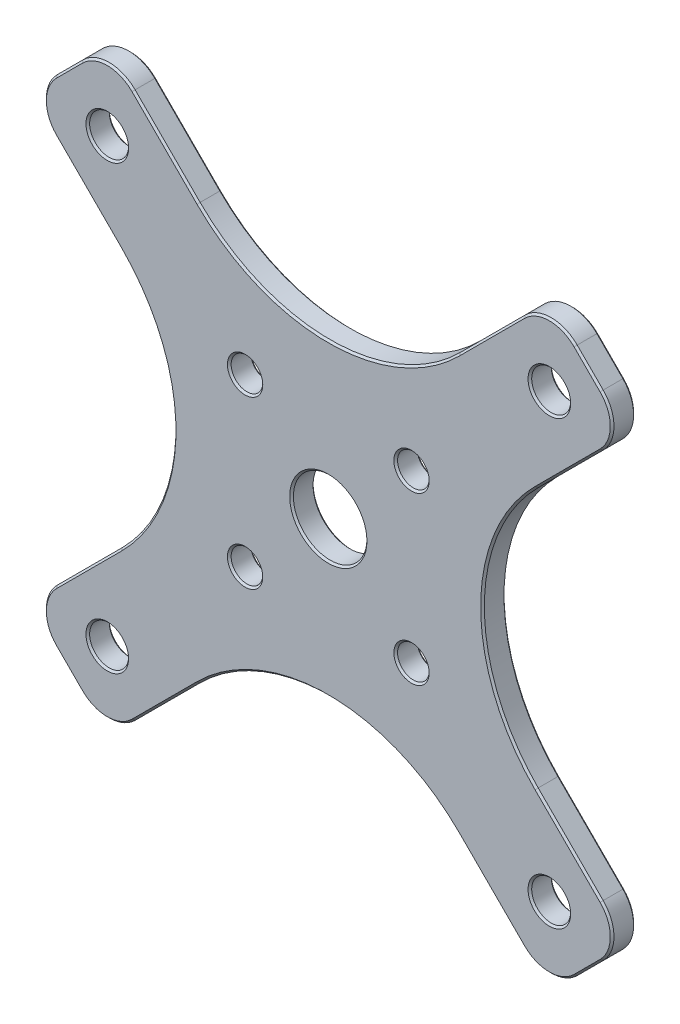
SolidWorks part; units mm, degrees
ref_plane "Front Plane" through (0, 0, 0) normal (0, 0, 1) x (1, 0, 0)
ref_plane "Top Plane" through (0, 0, 0) normal (0, 1, 0) x (1, 0, 0)
ref_plane "Right Plane" through (0, 0, 0) normal (1, 0, 0) x (0, 0, -1)
sketch "Sketch1" plane through (0, 0, 0) normal (0, 0, 1) x (1, 0, 0)
  line L0 (0, 10.6066) -> (30.052, 40.6586)
  line L1 (30.052, 40.6586) -> (40.6586, 30.052)
  line L2 (40.6586, 30.052) -> (10.6066, 0)
  line L3 (10.6066, 0) -> (40.6586, -30.052)
  line L4 (40.6586, -30.052) -> (30.052, -40.6586)
  line L5 (30.052, -40.6586) -> (0, -10.6066)
  line L6 (0, -10.6066) -> (-30.052, -40.6586)
  line L7 (-30.052, -40.6586) -> (-40.6586, -30.052)
  line L8 (-40.6586, -30.052) -> (-10.6066, 0)
  line L9 (-10.6066, 0) -> (-40.6586, 30.052)
  line L10 (-40.6586, 30.052) -> (-30.052, 40.6586)
  line L11 (-30.052, 40.6586) -> (0, 10.6066)
  line L12 (-35.3553, -35.3553) -> (35.3553, 35.3553) construction
  line L13 (-35.3553, 35.3553) -> (35.3553, -35.3553) construction
  line L14 (0, 0) -> (50, 0) construction
  circle A0 centre (0, 0) radius 5
  circle A1 centre (0, 0) radius 50 construction
  point P19 (0, 0)
  dimension "D1" = 10
  dimension "D3" = 100
  dimension "D2" = 45
  dimension "D4" = 15
extrude "Boss-Extrude1" add sketch "Sketch1" along normal mid plane 3.175
sketch "Sketch4" plane through (0, 0, 1.5875) normal (0, 0, 1) x (1, 0, 0)
  line L0 (0, 0) -> (11.3137, 11.3137) construction
  line L2 (0, 0) -> (-11.3137, -11.3137) construction
  line L4 (0, 0) -> (11.3137, -11.3137) construction
  line L6 (0, 0) -> (-11.3137, 11.3137) construction
  line L8 (10.6066, 0) -> (40.6586, 30.052) construction
  circle A0 centre (0, 0) radius 16 construction
  point P5 (11.3137, 11.3137)
  point P7 (11.3137, -11.3137)
  point P9 (-11.3137, -11.3137)
  point P11 (-11.3137, 11.3137)
  dimension "D1" = 32
hole_wizard "M4 Clearance Hole1" positions "Sketch4" profile "Sketch3" hole size "M4" standard "ANSI Metric" end condition through all
sketch "Sketch3" plane through (-11.3137, 11.3137, 1.5875) normal (1, 0, 0) x (0, -1, 0)
  line L0 (0, 0) -> (0, 3.175)
  line L1 (0, 3.175) -> (2.15, 3.175)
  line L2 (2.15, 3.175) -> (2.15, 0)
  line L5 (2.15, 0) -> (0, 0)
  line L11 (0, -6.35) -> (0, 107.95) construction
  dimension "Thru Hole Dia." = 4.3
  dimension "Thru Hole Depth" = 3.175
sketch "Sketch7" plane through (0, 0, -1.5875) normal (0, 0, -1) x (-1, 0, 0)
  line L0 (0, 0) -> (30.052, -30.052) construction
  line L3 (0, 0) -> (30.052, 30.052) construction
  line L4 (0, 0) -> (-30.052, 30.052) construction
  line L6 (0, 0) -> (-30.052, -30.052) construction
  line L8 (0, 10.6066) -> (30.052, 40.6586) construction
  line L9 (10.6066, 0) -> (40.6586, -30.052) construction
  circle A0 centre (0, 0) radius 42.5 construction
  point P0 (-30.052, 30.052)
  point P2 (30.052, 30.052)
  point P4 (30.052, -30.052)
  point P6 (-30.052, -30.052)
  dimension "D1" = 85
hole_wizard "M5 Clearance Hole1" positions "Sketch7" profile "Sketch6" hole size "M5" standard "ANSI Metric" end condition through all
sketch "Sketch6" plane through (30.052, 30.052, -1.5875) normal (1, 0, 0) x (0, 1, 0)
  line L0 (0, 0) -> (0, 3.175)
  line L1 (0, 3.175) -> (2.65, 3.175)
  line L2 (2.65, 3.175) -> (2.65, 0)
  line L5 (2.65, 0) -> (0, 0)
  line L11 (0, -6.35) -> (0, 107.95) construction
  dimension "Thru Hole Dia." = 5.3
  dimension "Thru Hole Depth" = 3.175
fillet "Fillet1" radius 25 4 edges at (-10.6066, 0, 0) (0, -10.6066, 0) (10.6066, 0, 0) (0, 10.6066, 0)
fillet "Fillet2" radius 5 8 edges at (40.6586, -30.052, 0) (30.052, -40.6586, 0) (-30.052, -40.6586, 0) (-40.6586, -30.052, 0) (-40.6586, 30.052, 0) (-30.052, 40.6586, 0) (30.052, 40.6586, 0) (40.6586, 30.052, 0)
chamfer "Chamfer1" distance 0.25 angle 45 66 edges at (5, 0, -1.5875) (20.9619, 0, -1.5875) (32.7037, 22.0971, -1.5875) (38.5876, 30.052, -1.5875) (35.3553, 35.3553, -1.5875) (30.052, 38.5876, -1.5875) (22.0971, 32.7037, -1.5875) (0, 20.9619, -1.5875) (-22.0971, 32.7037, -1.5875) (-30.052, 38.5876, -1.5875) (-35.3553, 35.3553, -1.5875) (-38.5876, 30.052, -1.5875) (-32.7037, 22.0971, -1.5875) (-20.9619, 0, -1.5875) (-32.7037, -22.0971, -1.5875) (-38.5876, -30.052, -1.5875) (-35.3553, -35.3553, -1.5875) (-30.052, -38.5876, -1.5875) (-22.0971, -32.7037, -1.5875) (0, -20.9619, -1.5875) (22.0971, -32.7037, -1.5875) (30.052, -38.5876, -1.5875) (35.3553, -35.3553, -1.5875) (38.5876, -30.052, -1.5875) (32.7037, -22.0971, -1.5875) (-9.1637, 11.3137, -1.5875) (-9.1637, -11.3137, -1.5875) (13.4637, -11.3137, -1.5875) (13.4637, 11.3137, -1.5875) (27.402, -30.052, -1.5875) (-32.702, -30.052, -1.5875) (-32.702, 30.052, -1.5875) (27.402, 30.052, -1.5875) (27.402, 30.052, 1.5875) (-32.702, 30.052, 1.5875) (-32.702, -30.052, 1.5875) (27.402, -30.052, 1.5875) (13.4637, 11.3137, 1.5875) (13.4637, -11.3137, 1.5875) (-9.1637, -11.3137, 1.5875) (-9.1637, 11.3137, 1.5875) (30.052, -38.5876, 1.5875) (22.0971, -32.7037, 1.5875) (0, -20.9619, 1.5875) (-22.0971, -32.7037, 1.5875) (-30.052, -38.5876, 1.5875) (-35.3553, -35.3553, 1.5875) (-38.5876, -30.052, 1.5875) (-32.7037, -22.0971, 1.5875) (-20.9619, 0, 1.5875) (-32.7037, 22.0971, 1.5875) (-38.5876, 30.052, 1.5875) (-35.3553, 35.3553, 1.5875) (-30.052, 38.5876, 1.5875) (-22.0971, 32.7037, 1.5875) (0, 20.9619, 1.5875) (22.0971, 32.7037, 1.5875) (30.052, 38.5876, 1.5875) (35.3553, 35.3553, 1.5875) (38.5876, 30.052, 1.5875) (32.7037, 22.0971, 1.5875) (20.9619, 0, 1.5875) (32.7037, -22.0971, 1.5875) (38.5876, -30.052, 1.5875) (35.3553, -35.3553, 1.5875) (5, 0, 1.5875)
